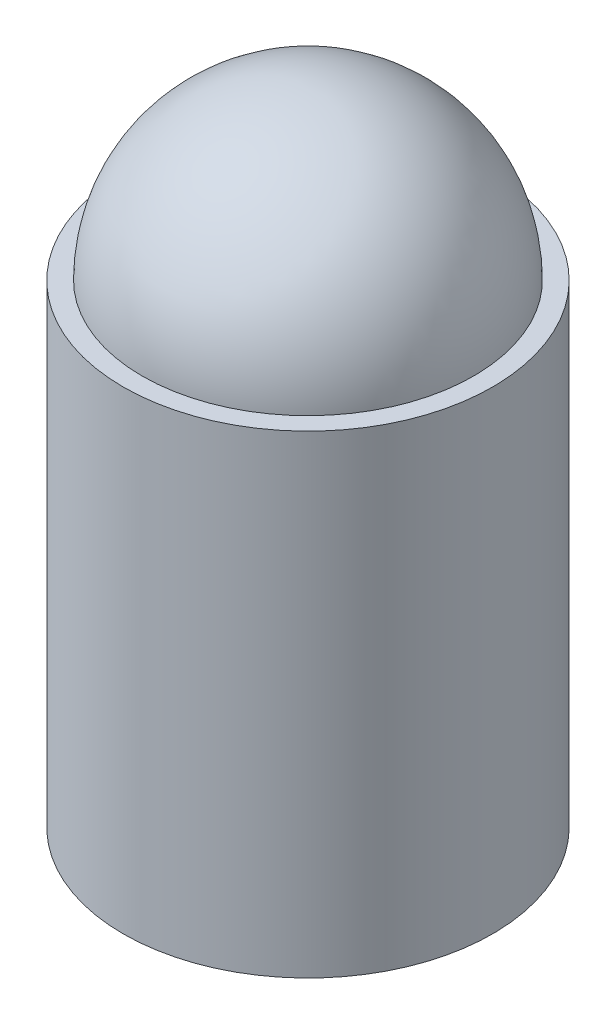
SolidWorks part; units mm, degrees
ref_plane "Front Plane" through (0, 0, 0) normal (0, 0, 1) x (1, 0, 0)
ref_plane "Top Plane" through (0, 0, 0) normal (0, 1, 0) x (1, 0, 0)
ref_plane "Right Plane" through (0, 0, 0) normal (1, 0, 0) x (0, 0, -1)
sketch "Sketch1" plane through (0, 0, 0) normal (0, 1, 0) x (1, 0, 0)
  line L0 (-4.445, 0) -> (4.445, 0) construction
  line L1 (-4.445, 0) -> (4.445, 0)
  arc A0 (-4.445, 0) -> (4.445, 0) centre (0, 0) ccw
  dimension "D1" = 8.89
revolve "Revolve4" add sketch "Sketch1" angle 360 about L0
sketch "Sketch2" plane through (0, 0, 0) normal (0, 1, 0) x (1, 0, 0)
  circle A0 centre (0, 0) radius 4.953
  circle A1 centre (0, 0) radius 4.445 construction
  dimension "D1" = 0.508
extrude "Boss-Extrude1" add sketch "Sketch2" against normal blind 12.7
